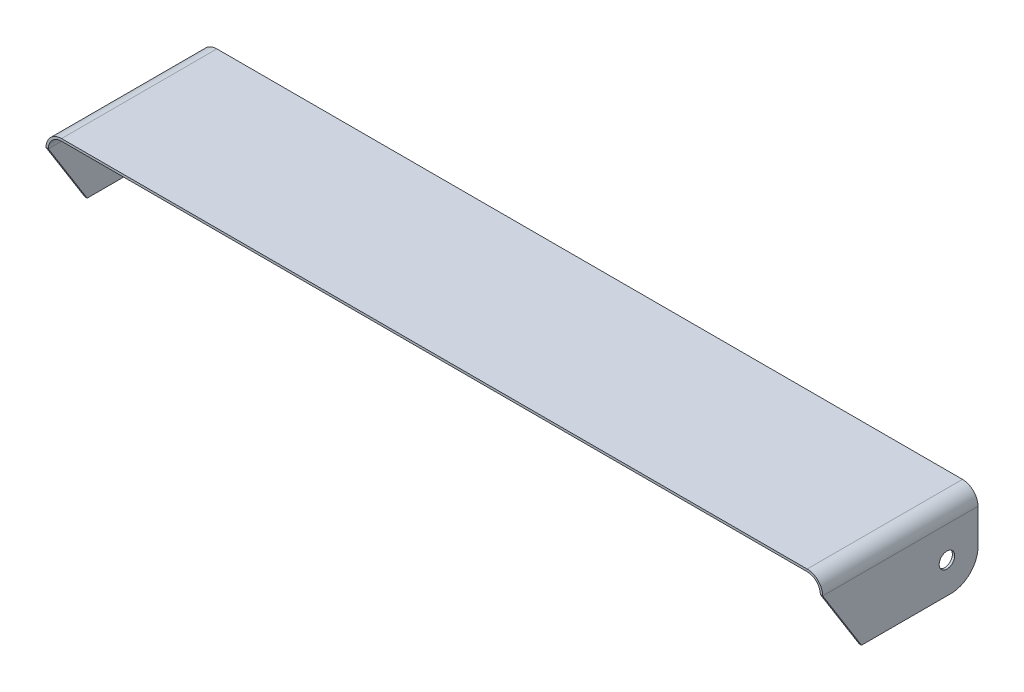
SolidWorks part; units mm, degrees
ref_plane "Front Plane" through (0, 0, 0) normal (0, 0, 1) x (1, 0, 0)
ref_plane "Top Plane" through (0, 0, 0) normal (0, 1, 0) x (1, 0, 0)
ref_plane "Right Plane" through (0, 0, 0) normal (1, 0, 0) x (0, 0, -1)
sketch "Sketch1" plane through (0, 0, 0) normal (0, 0, 1) x (1, 0, 0)
  line L0 (-500, 0) -> (-500, 80)
  line L1 (-480, 100) -> (480, 100)
  line L2 (500, 80) -> (500, 0)
  line L3 (-497, 0) -> (-497, 80)
  line L4 (-480, 97) -> (480, 97)
  line L5 (497, 80) -> (497, 0)
  line L6 (-500, 0) -> (-497, 0)
  line L7 (497, 0) -> (500, 0)
  arc A0 (480, 100) -> (500, 80) centre (480, 80) cw
  arc A1 (-500, 80) -> (-480, 100) centre (-480, 80) cw
  arc A2 (-497, 80) -> (-480, 97) centre (-480, 80) cw
  arc A3 (480, 97) -> (497, 80) centre (480, 80) cw
  point P8 (500, 100)
  point P11 (-500, 100)
  dimension "D4" = 20
  dimension "D1" = 1000
  dimension "D2" = 100
  dimension "D3" = 500
  dimension "D5" = 3
extrude "Boss-Extrude1" add sketch "Sketch1" along normal mid plane 200
sketch "Sketch2" plane through (500, 0, 0) normal (1, 0, 0) x (0, 0, -1)
  line L0 (-100, 80) -> (-100, 0)
  line L1 (-100, 0) -> (-100, 80) construction
  line L2 (-100, 0) -> (-50, 0)
  line L3 (-100, 0) -> (100, 0) construction
  line L4 (-50, 0) -> (-100, 80)
  dimension "D1" = 80
  dimension "D2" = 50
extrude "Cut-Extrude1" cut sketch "Sketch2" against normal through all
sketch "Sketch3" plane through (500, 0, 0) normal (1, 0, 0) x (0, 0, -1)
  line L0 (100, 0) -> (100, 80) construction
  line L1 (-100, 100) -> (100, 100) construction
  circle A0 centre (60, 40) radius 10
  dimension "D3" = 20
  dimension "D1" = 40
  dimension "D2" = 60
extrude "Cut-Extrude2" cut sketch "Sketch3" against normal through all
fillet "Fillet1" radius 35 1 edges at (498.5, 0, -100)
fillet "Fillet2" radius 35 1 edges at (-498.5, 0, -100)
